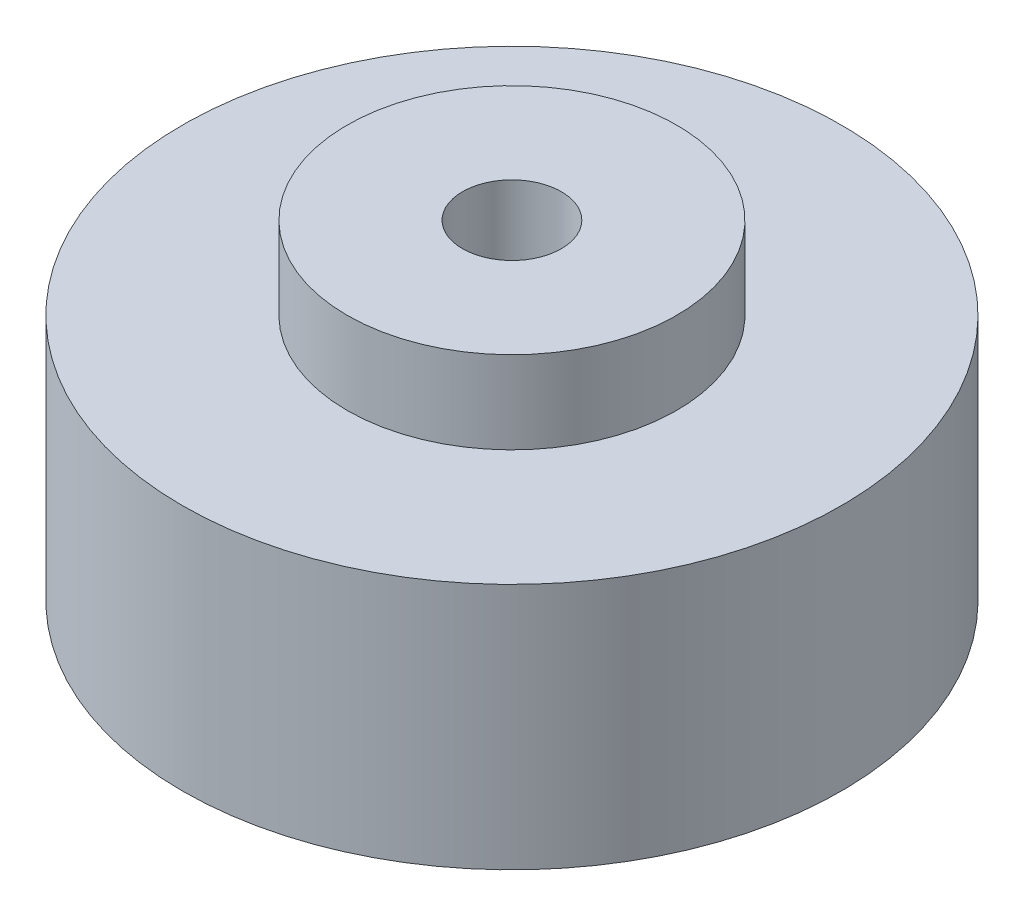
SolidWorks part; units mm, degrees
material "1060 Alloy"
ref_plane "Front Plane" through (0, 0, 0) normal (0, 0, 1) x (1, 0, 0)
ref_plane "Top Plane" through (0, 0, 0) normal (0, 1, 0) x (1, 0, 0)
ref_plane "Right Plane" through (0, 0, 0) normal (1, 0, 0) x (0, 0, -1)
sketch "Sketch1" plane through (0, 0, 0) normal (0, 1, 0) x (1, 0, 0)
  circle A0 centre (0, 0) radius 20
  dimension "D1" = 40
extrude "Extrude1" add sketch "Sketch1" against normal blind 15
sketch "Sketch2" plane through (0, 0, 0) normal (0, 1, 0) x (1, 0, 0)
  circle A0 centre (0, 0) radius 10
  dimension "D2" = 20
extrude "Extrude2" add sketch "Sketch2" along normal blind 5
sketch "Sketch3" plane through (0, 5, 0) normal (0, 1, 0) x (1, 0, 0)
  circle A0 centre (0, 0) radius 3
  dimension "D2" = 6
extrude "Cut-Extrude1" cut sketch "Sketch3" against normal through all
